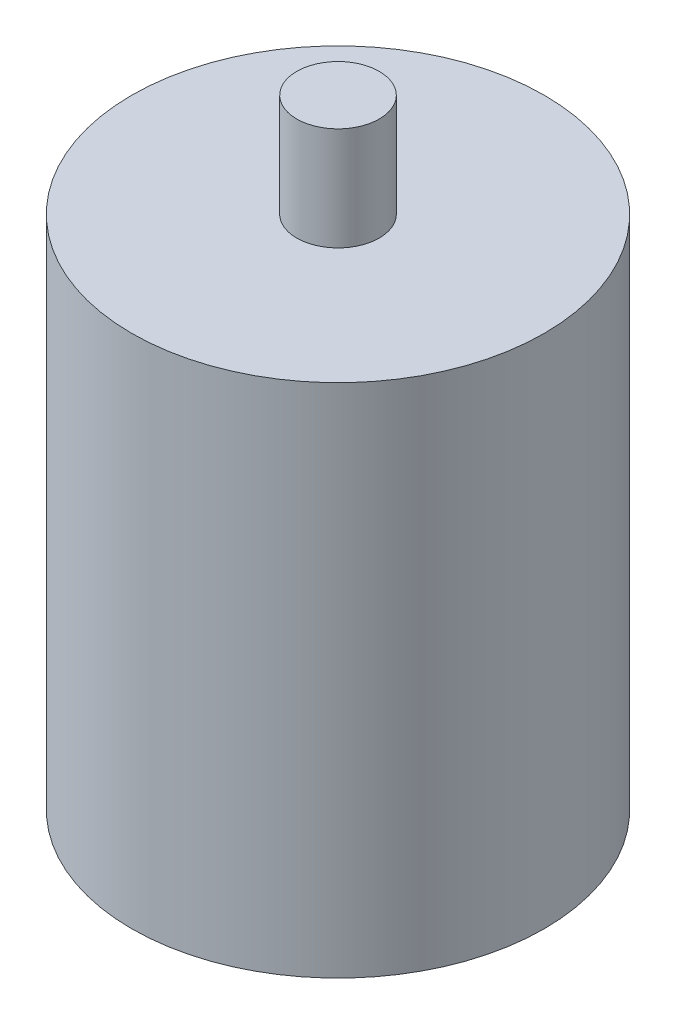
SolidWorks part; units mm, degrees
material "灰铸铁"
ref_plane "前视基准面" through (0, 0, 0) normal (0, 0, 1) x (1, 0, 0)
ref_plane "上视基准面" through (0, 0, 0) normal (0, 1, 0) x (1, 0, 0)
ref_plane "右视基准面" through (0, 0, 0) normal (1, 0, 0) x (0, 0, -1)
other "Configuration Table"
sketch "草图3" plane through (0, 0, 0) normal (0, 1, 0) x (1, 0, 0)
  circle A0 centre (0, 0) radius 20
  dimension "D1" = 40
extrude "凸台-拉伸3" add sketch "草图3" along normal blind 50
sketch "草图4" plane through (0, 0, 0) normal (0, -1, 0) x (1, 0, 0)
  circle A0 centre (0, 0) radius 3
  dimension "D1" = 6
extrude "凸台-拉伸4" add sketch "草图4" along normal blind 5
sketch "草图5" plane through (0, 50, 0) normal (0, 1, 0) x (1, 0, 0)
  circle A0 centre (0, 0) radius 4
  dimension "D1" = 8
extrude "凸台-拉伸5" add sketch "草图5" along normal blind 10
